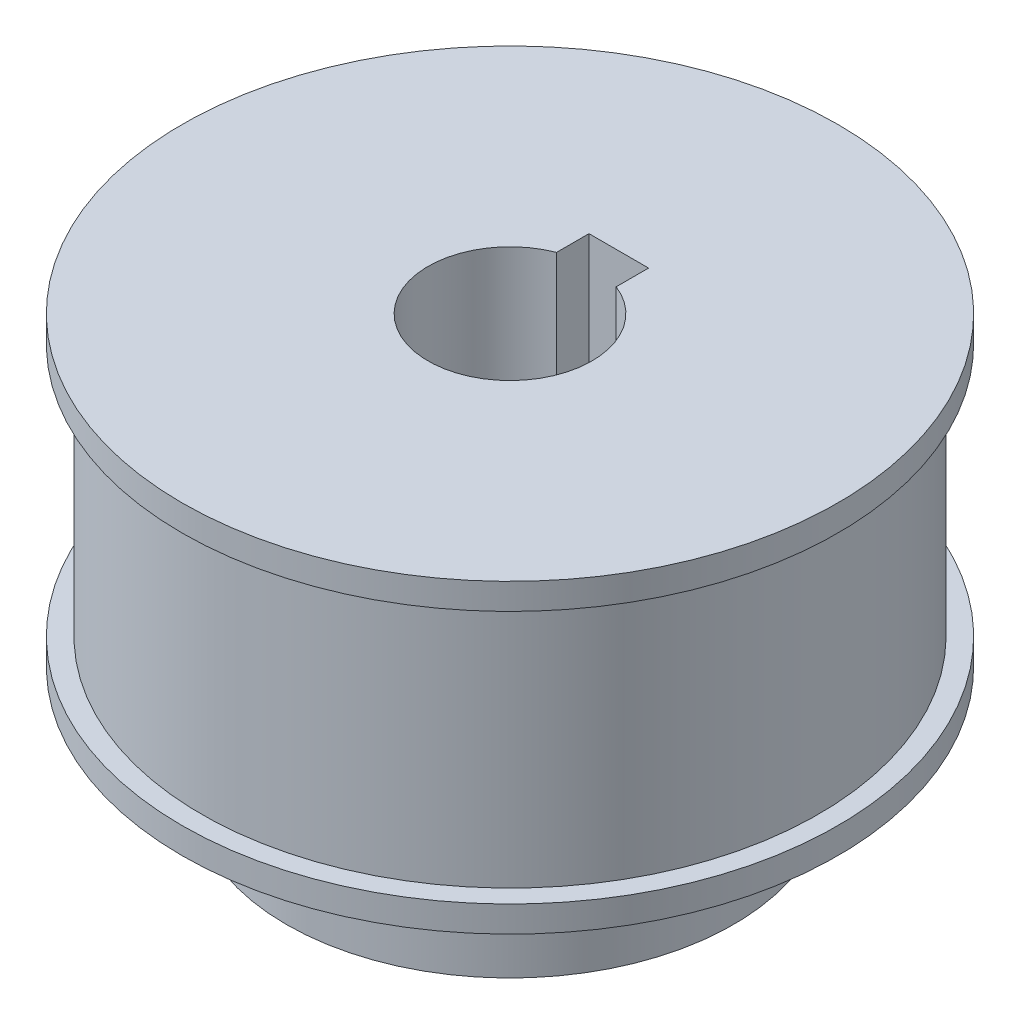
SolidWorks part; units mm, degrees
material "1023 Carbon Steel Sheet (SS)"
ref_plane "Front Plane" through (0, 0, 0) normal (0, 0, 1) x (1, 0, 0)
ref_plane "Top Plane" through (0, 0, 0) normal (0, 1, 0) x (1, 0, 0)
ref_plane "Right Plane" through (0, 0, 0) normal (1, 0, 0) x (0, 0, -1)
sketch "Sketch1" plane through (0, 0, 0) normal (0, 0, 1) x (1, 0, 0)
  line L0 (4, 0) -> (15, 0)
  line L1 (15, 0) -> (15, 7.5)
  line L2 (15, 7.5) -> (22, 7.5)
  line L3 (22, 7.5) -> (22, 9.25)
  line L4 (22, 9.25) -> (20.69, 9.25)
  line L5 (20.69, 9.25) -> (20.69, 26.25)
  line L6 (20.69, 26.25) -> (22, 26.25)
  line L7 (22, 26.25) -> (22, 28)
  line L8 (22, 28) -> (4, 28)
  line L9 (4, 28) -> (4, 0)
  line L10 (0, 0) -> (0, 38.5) construction
  dimension "D1" = 4
  dimension "D2" = 22
  dimension "D3" = 28
  dimension "D4" = 20.5
  dimension "D5" = 17
  dimension "D6" = 15
  dimension "D7" = 20.69
revolve "Revolve1" add sketch "Sketch1" angle 360 about L10
sketch "Sketch2" plane through (0, 28, 0) normal (0, 1, 0) x (1, 0, 0)
  circle A0 centre (0, 0) radius 5.5
  dimension "D1" = 11
extrude "Cut-Extrude1" cut sketch "Sketch2" against normal blind 33
sketch "Sketch3" plane through (0, 28, 0) normal (0, 1, 0) x (1, 0, 0)
  line L1 (-2, 5.1235) -> (2, 5.1235)
  line L2 (-2, 5.1235) -> (-2, 7.3)
  line L3 (-2, 7.3) -> (2, 7.3)
  line L4 (2, 5.1235) -> (2, 7.3)
  circle A0 centre (0, 0) radius 5.5 construction
  circle A1 centre (0, 0) radius 5.5
  circle M6 centre (0, 0) radius 5.5
  dimension "D1" = 1.8
  dimension "D2" = 4
extrude "Cut-Extrude2" cut sketch "Sketch3" against normal blind 33 contours L4 L3 L2 M6
sketch "Sketch4" plane through (0, 0, -7.3) normal (0, 0, 1) x (1, 0, 0)
  line L0 (0, 0) -> (0, 3.75) construction
  line L1 (-15, 0) -> (15, 0) construction
  circle A0 centre (0, 3.75) radius 1.2
  dimension "D2" = 2.4
  dimension "D1" = 3.75
extrude "Cut-Extrude3" cut sketch "Sketch4" against normal blind 80
sketch "Sketch5" [suppressed] plane through (0, 0, 0) normal (0, 0, 1) x (1, 0, 0)
  line L0 (-15, 0) -> (15, 0) construction
  line L1 (-15, 0) -> (-15, 7.5) construction
  line L2 (-15, 7.5) -> (15, 7.5) construction
  circle A0 centre (0, 3.5267) radius 2
  dimension "D1" = 4
  dimension "D2" = 3.5267
  dimension "D3" = 7.5
extrude "Cut-Extrude4" [suppressed] cut sketch "Sketch5" against normal blind 18
sketch "Sketch6" [suppressed] plane through (0, 0, 0) normal (1, 0, 0) x (0, 0, -1)
  line L0 (-15, 0) -> (-15, 7.5) construction
  line L1 (-15, 7.5) -> (15, 7.5) construction
  line L2 (-22, 7.5) -> (22, 7.5) construction
  line L3 (-15, 0) -> (15, 0) construction
  circle A0 centre (0, 3.75) radius 2
  dimension "D1" = 4
  dimension "D2" = 7.5
  dimension "D3" = 3.75
extrude "Cut-Extrude5" [suppressed] cut sketch "Sketch6" against normal blind 18
equation "\"D3@Sketch6\"=\"D2@Sketch6\"/2"
